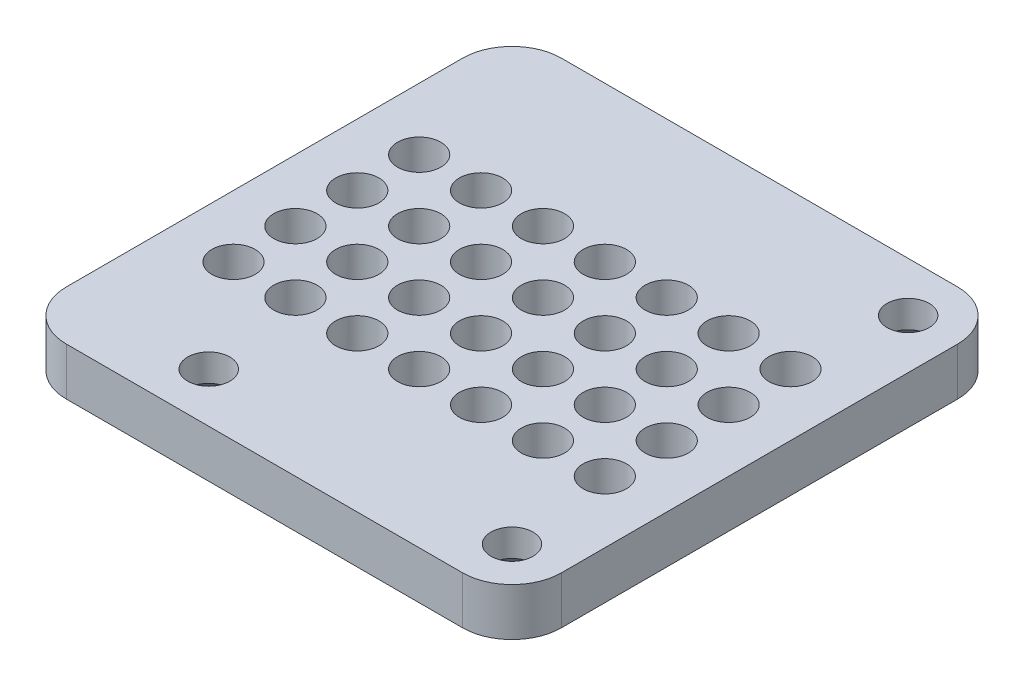
SolidWorks part; units mm, degrees
ref_plane "Front Plane" through (0, 0, 0) normal (0, 0, 1) x (1, 0, 0)
ref_plane "Top Plane" through (0, 0, 0) normal (0, 1, 0) x (1, 0, 0)
ref_plane "Right Plane" through (0, 0, 0) normal (1, 0, 0) x (0, 0, -1)
sketch "Sketch1" plane through (0, 0, 0) normal (0, 1, 0) x (1, 0, 0)
  line L1 (4, 0) -> (36, 0)
  line L2 (0, 4) -> (0, 36)
  line L3 (4, 40) -> (36, 40)
  line L4 (40, 4) -> (40, 36)
  arc A0 (4, 0) -> (0, 4) centre (4, 4) cw
  arc A1 (0, 36) -> (4, 40) centre (4, 36) cw
  arc A2 (36, 0) -> (40, 4) centre (36, 4) ccw
  arc A3 (36, 40) -> (40, 36) centre (36, 36) cw
  circle A4 centre (11.5, 4) radius 1.6
  circle A5 centre (36, 4) radius 1.6
  circle A6 centre (36, 36) radius 1.6
  point P7 (0, 0)
  point P10 (0, 40)
  dimension "D2" = 4
  dimension "D3" = 3.2
  dimension "D1" = 40
  dimension "D4" = 4
  dimension "D5" = 11.5
  dimension "D6" = 36
  dimension "D7" = 36
extrude "Boss-Extrude1" add sketch "Sketch1" along normal blind 3.85
hole_wizard "CSK for M3 Countersunk Flat Head Screw1" positions "Sketch2" profile "Sketch3" countersink size "M3" standard "ISO" end condition through all
sketch "Sketch2" plane through (0, 0, 0) normal (0, -1, 0) x (-1, 0, 0)
  point P0 (-11.5, 4)
  point P3 (-36, 4)
  point P6 (-36, 36)
sketch "Sketch3" plane through (11.5, 0, -4) normal (1, 0, 0) x (0, 0, -1)
  line L0 (0, 0) -> (0, 3.85)
  line L1 (0, 3.85) -> (1.7, 3.85)
  line L2 (1.7, 3.85) -> (1.7, 1.65)
  line L3 (1.7, 1.65) -> (3.35, 0)
  line L5 (3.35, 0) -> (0, 0)
  line L6 (-1.7, 1.65) -> (-3.35, 0) construction
  line L11 (0, -6.35) -> (0, 107.95) construction
  dimension "Thru Hole Dia." = 3.4
  dimension "Thru Hole Depth" = 3.85
  dimension "Near C'Sink Dia." = 6.7
  dimension "Near C'Sink Angle" = 90
sketch "Sketch4" plane through (0, 3.85, 0) normal (0, 1, 0) x (1, 0, 0)
  line L0 (5, 22.5) -> (5, 17.5) construction
  line L1 (0, 36) -> (0, 4) construction
  line L4 (4, 0) -> (36, 0) construction
  circle A0 centre (5, 22.5) radius 1.75
  circle A1 centre (10, 22.5) radius 1.75
  circle A2 centre (5, 17.5) radius 1.75
  circle A3 centre (10, 17.5) radius 1.75
  circle A4 centre (30, 17.5) radius 1.75
  circle A5 centre (35, 17.5) radius 1.75
  circle A6 centre (30, 22.5) radius 1.75
  circle A7 centre (35, 22.5) radius 1.75
  circle A8 centre (15, 22.5) radius 1.75
  circle A9 centre (15, 17.5) radius 1.75
  circle A10 centre (20, 22.5) radius 1.75
  circle A11 centre (20, 17.5) radius 1.75
  circle A12 centre (25, 22.5) radius 1.75
  circle A13 centre (25, 17.5) radius 1.75
  circle A14 centre (5, 27.5) radius 1.75
  circle A15 centre (10, 27.5) radius 1.75
  circle A16 centre (30, 27.5) radius 1.75
  circle A17 centre (35, 27.5) radius 1.75
  circle A18 centre (15, 27.5) radius 1.75
  circle A19 centre (20, 27.5) radius 1.75
  circle A20 centre (25, 27.5) radius 1.75
  circle A28 centre (35, 32.5) radius 1.75 [skipped]
  circle A29 centre (5, 12.5) radius 1.75
  circle A30 centre (10, 12.5) radius 1.75
  circle A31 centre (30, 12.5) radius 1.75
  circle A32 centre (35, 12.5) radius 1.75
  circle A33 centre (15, 12.5) radius 1.75
  circle A34 centre (20, 12.5) radius 1.75
  circle A35 centre (25, 12.5) radius 1.75
  circle A43 centre (10, 7.5) radius 1.75 [skipped]
  circle A44 centre (35, 7.5) radius 1.75 [skipped]
  circle A45 centre (10, 32.5) radius 1.75 [skipped]
  circle A46 centre (5, 7.5) radius 1.75 [skipped]
  circle A47 centre (30, 7.5) radius 1.75 [skipped]
  circle A48 centre (15, 7.5) radius 1.75 [skipped]
  circle A49 centre (20, 7.5) radius 1.75 [skipped]
  circle A50 centre (25, 7.5) radius 1.75 [skipped]
  circle A51 centre (5, 32.5) radius 1.75 [skipped]
  circle A52 centre (30, 32.5) radius 1.75 [skipped]
  circle A53 centre (15, 32.5) radius 1.75 [skipped]
  circle A54 centre (25, 32.5) radius 1.75 [skipped]
  circle A55 centre (20, 32.5) radius 1.75 [skipped]
  point P10 (0, 20)
  point P11 (5, 20)
  dimension "D1" = 3.5
  dimension "D2" = 5
  dimension "D3" = 5
  dimension "D4" = 5
  dimension "D6" = 5
  dimension "D8" = 5
  dimension "D10" = 5
  dimension "D11" = 5
  dimension "D12" = 5
  dimension "D5" = 4
  dimension "D7" = 3
  dimension "D9" = 3
extrude "Cut-Extrude1" cut sketch "Sketch4" against normal blind 12.5
